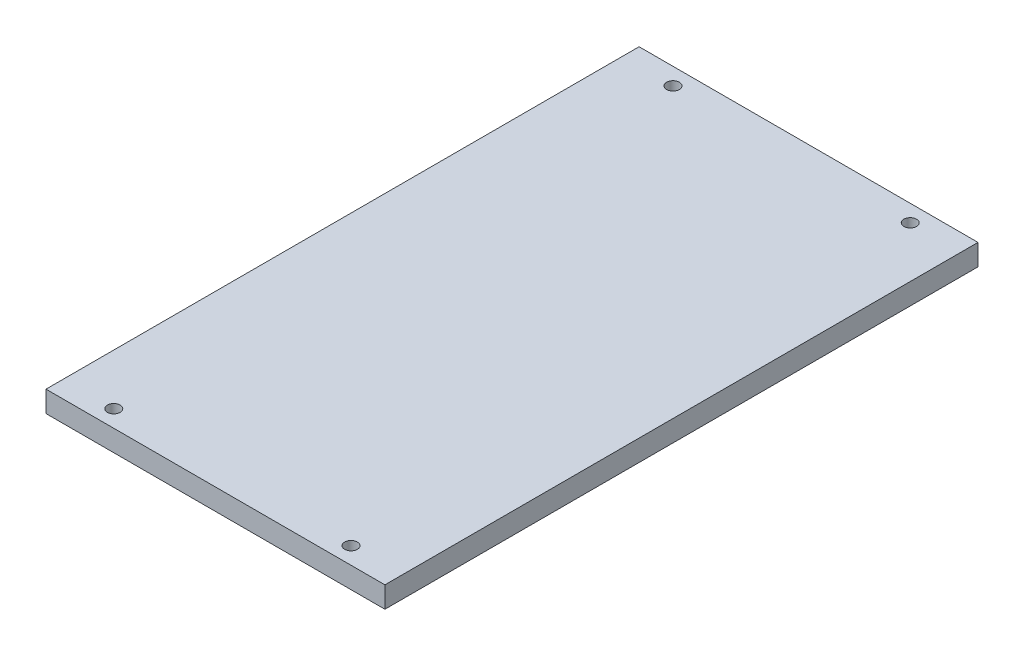
SolidWorks part; units mm, degrees
material "ABS PC"
ref_plane "Front Plane" through (0, 0, 0) normal (0, 0, 1) x (1, 0, 0)
ref_plane "Top Plane" through (0, 0, 0) normal (0, 1, 0) x (1, 0, 0)
ref_plane "Right Plane" through (0, 0, 0) normal (1, 0, 0) x (0, 0, -1)
sketch "Sketch1" plane through (0, 0, 0) normal (0, 1, 0) x (1, 0, 0)
  line L1 (0, 0) -> (-80, 0)
  line L2 (0, 0) -> (0, 140)
  line L3 (0, 140) -> (-80, 140)
  line L4 (-80, 0) -> (-80, 140)
  dimension "D1" = 140
  dimension "D2" = 80
extrude "Boss-Extrude1" add sketch "Sketch1" along normal blind 5
sketch "Sketch2" plane through (0, 5, 0) normal (0, 1, 0) x (1, 0, 0)
  line L0 (0, 140) -> (-80, 140) construction
  line L1 (-80, 140) -> (-80, 0) construction
  circle A0 centre (-68, 136) radius 1.5
  dimension "D1" = 3
  dimension "D2" = 4
  dimension "D3" = 12
extrude "Cut-Extrude1" cut sketch "Sketch2" against normal through all
sketch "Sketch3" plane through (0, 5, 0) normal (0, 1, 0) x (1, 0, 0)
  line L0 (0, 0) -> (0, 140) construction
  line L1 (0, 140) -> (-80, 140) construction
  circle A0 centre (-12, 136) radius 1.5
  dimension "D1" = 3
  dimension "D2" = 12
  dimension "D3" = 4
extrude "Cut-Extrude2" cut sketch "Sketch3" against normal through all
ref_plane "Plane1" through (0, 0, -70) normal (0, 0, 1) x (1, 0, 0)
mirror "Mirror1" about plane through (0, 0, -70) normal (0, 0, 1) of "Cut-Extrude2", "Cut-Extrude1"
